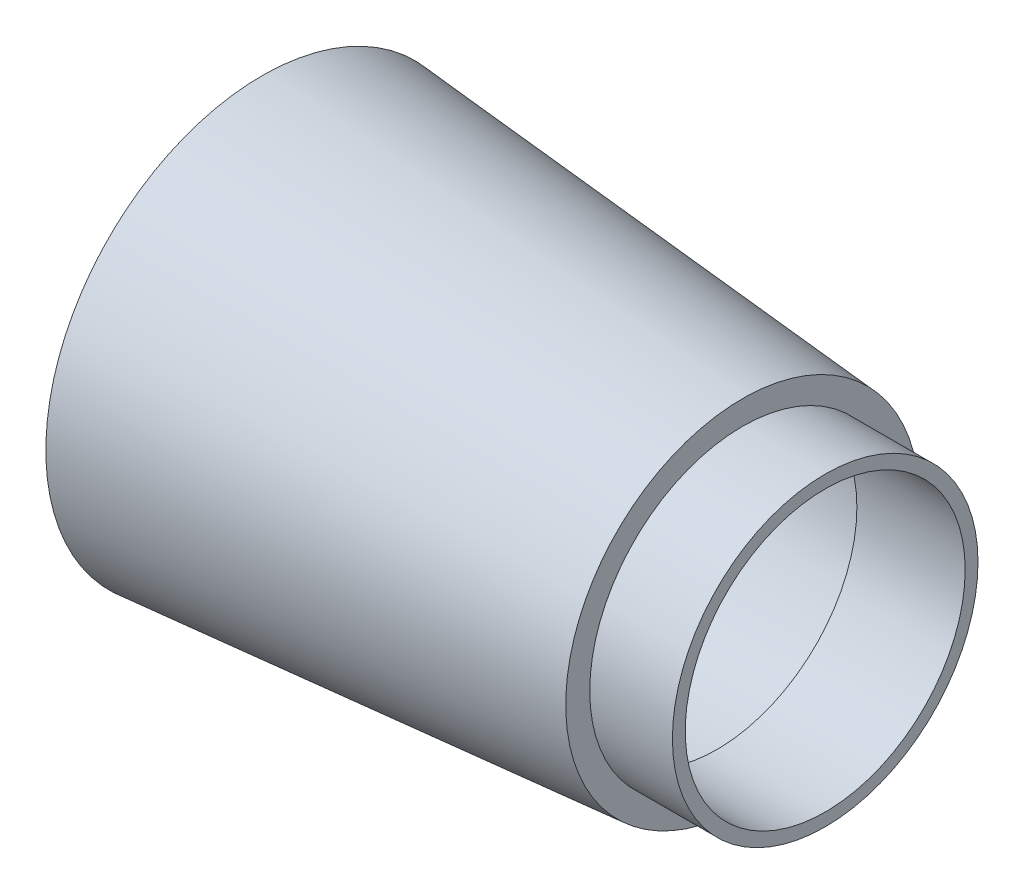
SolidWorks part; units mm, degrees
ref_plane "Front Plane" through (0, 0, 0) normal (0, 0, 1) x (1, 0, 0)
ref_plane "Top Plane" through (0, 0, 0) normal (0, 1, 0) x (1, 0, 0)
ref_plane "Right Plane" through (0, 0, 0) normal (1, 0, 0) x (0, 0, -1)
sketch "Sketch1" plane through (0, 0, 0) normal (0, 0, 1) x (1, 0, 0)
  line L0 (-12.065, 11.43) -> (-12.065, 10.16)
  line L1 (44.7264, 0) -> (-69.8413, 0) construction
  line L2 (13.335, 9.3472) -> (13.335, 8.0772)
  line L3 (-12.065, 0) -> (14.2126, 0) construction
  line L4 (-1.0793, 10.5292) -> (-1.0793, 0)
  line L5 (13.335, 9.3472) -> (-12.065, 11.43)
  line L6 (-12.065, 10.16) -> (13.335, 8.0772)
  line L7 (-1.0793, 0) -> (0.635, 0)
  line L8 (0.635, 0) -> (0.635, 10.3886)
  line L9 (0.635, 10.3886) -> (-1.0793, 10.5292)
  line L11 (17.6724, 7.3996) -> (11.98, 7.3996)
  line L12 (11.98, 7.3996) -> (11.98, 8.1883)
  line L13 (11.98, 8.1883) -> (13.335, 8.0772)
  line L14 (13.335, 8.0772) -> (17.7046, 8.0772)
  line L15 (17.7046, 7.3996) -> (17.6724, 7.3996)
  line L16 (17.7046, 8.0772) -> (17.7046, 7.3996)
  dimension "D1" = 25.4
  dimension "D2" = 1.27
  dimension "D3" = 11.43
  dimension "D4" = 9.3472
  dimension "D5" = 1.27
revolve "Revolve4" add sketch "Sketch1" angle 360 about L1
sketch "Sketch2" plane through (0.635, 0, 0) normal (1, 0, 0) x (0, 0, -1)
  line L3 (-0.3129, 0) -> (0.3129, 0)
  line L4 (-0.3129, 0) -> (-0.3129, 1.0082)
  line L5 (-0.3129, 1.0082) -> (0.3129, 1.0082)
  line L6 (0.3129, 0) -> (0.3129, 1.0082)
  line L9 (-0.3129, 1.0082) -> (0.3129, 1.0082)
  line L10 (-0.3129, 1.0082) -> (-0.3129, 0.7863)
  line L11 (-0.3129, 0.7863) -> (0.3129, 0.7863)
  line L12 (0.3129, 1.0082) -> (0.3129, 0.7863)
  point P3 (0, 0)
  point P8 (0, 0)
revolve "Revolve5" add sketch "Sketch2" angle 180 about L3
